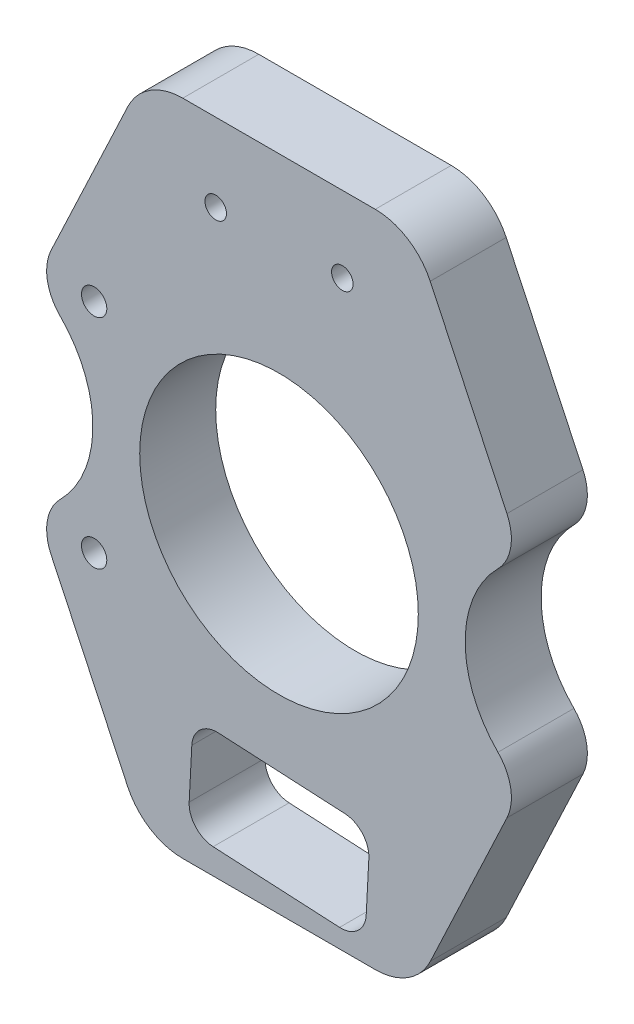
SolidWorks part; units mm, degrees
ref_plane "Płaszczyzna przednia" through (0, 0, 0) normal (0, 0, 1) x (1, 0, 0)
ref_plane "Płaszczyzna górna" through (0, 0, 0) normal (0, 1, 0) x (1, 0, 0)
ref_plane "Płaszczyzna prawa" through (0, 0, 0) normal (1, 0, 0) x (0, 0, -1)
sketch "Szkic1" plane through (0, 0, 0) normal (0, 0, 1) x (1, 0, 0)
  line L3 (0, 260) -> (0, 0) construction
  line L5 (0, 130) -> (-92.5, 130) construction
  line L6 (25, 230) -> (-113.1637, 230) construction
  line L7 (-38, 260) -> (38, 260)
  line L8 (59.7094, 246.2323) -> (90.0082, 181.9488)
  line L9 (59.7662, 13.7409) -> (90.0082, 77.9041)
  line L10 (0, 0) -> (38, 0)
  line L11 (-59.7662, 13.7409) -> (-90.0082, 77.9041)
  line L12 (-59.7094, 246.2323) -> (-90.0082, 181.9488)
  line L13 (-38, 0) -> (0, 0)
  line L14 (25, 230) -> (-114.4641, 227.5656) construction
  line L15 (-25, 30) -> (78.9798, 30) construction
  line L16 (-25, 30) -> (79.6859, 24.5136) construction
  circle A0 centre (0, 130) radius 55
  circle A2 centre (-73, 87) radius 5
  circle A3 centre (-73, 173) radius 5
  arc A4 (86.4422, 161.3009) -> (86.4422, 98.552) centre (118, 129.9265) ccw
  circle A5 centre (25, 230) radius 50 construction
  arc A6 (86.4422, 98.552) -> (90.0082, 77.9041) centre (73.5, 85.6849) cw
  arc A7 (86.4422, 161.3009) -> (90.0082, 181.9488) centre (73.5, 174.168) ccw
  circle A8 centre (25, 230) radius 4.25
  arc A9 (59.7094, 246.2323) -> (38, 260) centre (38, 236) ccw
  arc A11 (59.7662, 13.7409) -> (38, 0) centre (38.0693, 23.9999) cw
  arc A12 (-59.7662, 13.7409) -> (-38, 0) centre (-38.0693, 23.9999) ccw
  arc A13 (-86.4422, 98.552) -> (-90.0082, 77.9041) centre (-73.5, 85.6849) ccw
  arc A14 (-86.4422, 161.3009) -> (-86.4422, 98.552) centre (-118, 129.9265) cw
  arc A15 (-86.4422, 161.3009) -> (-90.0082, 181.9488) centre (-73.5, 174.168) cw
  arc A16 (-59.7094, 246.2323) -> (-38, 260) centre (-38, 236) cw
  circle A18 centre (-24.9924, 229.1274) radius 4.25
  circle A20 centre (-25, 30) radius 4.25
  circle A21 centre (-25, 30) radius 50 construction
  circle A22 centre (24.9315, 27.3832) radius 4.25
  point P23 (96.4639, 168.868)
  dimension "D1" = 18.25
  dimension "D2" = 110
  dimension "D3" = 1
  dimension "D6" = 44.5
  dimension "D7" = 10
  dimension "D10" = 38
  dimension "D4" = 24
  dimension "D11" = 48
  dimension "D12" = 130
  dimension "D13" = 73.5
  dimension "D16" = 73
  dimension "D17" = 8.5
  dimension "D18" = 118
  dimension "D5" = 8.5
  dimension "D19" = 100
  dimension "D20" = 3
  dimension "D21" = 8.5
  dimension "D22" = 8.5
  dimension "D23" = 30
  dimension "D24" = 27.3832
  dimension "D25" = 25
  dimension "D26" = 100
  dimension "D8" = 25
  dimension "D9" = 30
  dimension "D14" = 73.5
  dimension "D15" = 43
extrude "Dodanie-wyciągnięcie1" add sketch "Szkic1" along normal blind 30
sketch "Szkic2" plane through (0, 0, 30) normal (0, 0, 1) x (1, 0, 0)
  line L1 (0, 260) -> (0, -13.2421) construction
  line L2 (38, 260) -> (-38, 260) construction
  line L12 (-88.8511, 130) -> (90.6766, 130) construction
  point P4 (0, 230)
  point P19 (0, 245)
sketch "Szkic3" plane through (0, 0, 0) normal (0, 0, -1) x (-1, 0, 0)
  circle A0 centre (25, 30) radius 4
  circle A1 centre (-24.9315, 27.3832) radius 4
  circle A2 centre (24.9924, 229.1274) radius 4
  circle A3 centre (-25, 230) radius 4
ref_plane "Płaszczyzna1" through (-86.4422, 98.552, 0) normal (0, 0, -1) x (-1, 0, 0)
sketch "Szkic4" plane through (-86.4422, 98.552, 0) normal (0, 0, -1) x (-1, 0, 0)
  line L0 (-52.5369, -48.0578) -> (-50.4435, -88.003)
  line L1 (-122.441, -51.7213) -> (-120.3475, -91.6665)
  line L2 (-86.4422, 161.448) -> (-86.4422, -111.7941) construction
  line L3 (-122.441, -51.7213) -> (-52.5369, -48.0578)
  line L4 (-121.3943, -71.6939) -> (-51.4902, -68.0304) construction
  line L5 (-50.4435, -88.003) -> (-120.3475, -91.6665)
  point P2 (-51.4902, -68.0304)
  point P9 (-121.3943, -71.6939)
  point P13 (-86.4422, -69.8622)
  dimension "D1" = 70
  dimension "D2" = 40
extrude "Wytnij-wyciągnięcie1" cut sketch "Szkic4" against normal blind 30
fillet "Zaokrąglenie1" radius 10 4 edges at (33.9053, 6.8855, 15) (-35.9988, 10.549, 15) (-33.9053, 50.4942, 15) (35.9988, 46.8306, 15)
sketch "Szkic5" plane through (0, 0, 0) normal (0, 0, -1) x (-1, 0, 0)
  line L0 (1.5036, 0) -> (-1.415, 55.6904)
  line L1 (23.919, 49.9708) -> (-26.0125, 47.354) construction
  line L2 (-23.919, 7.4088) -> (26.0125, 10.0256) construction
  line L3 (38, 0) -> (-38, 0) construction
  point P7 (-1.0467, 48.6624)
